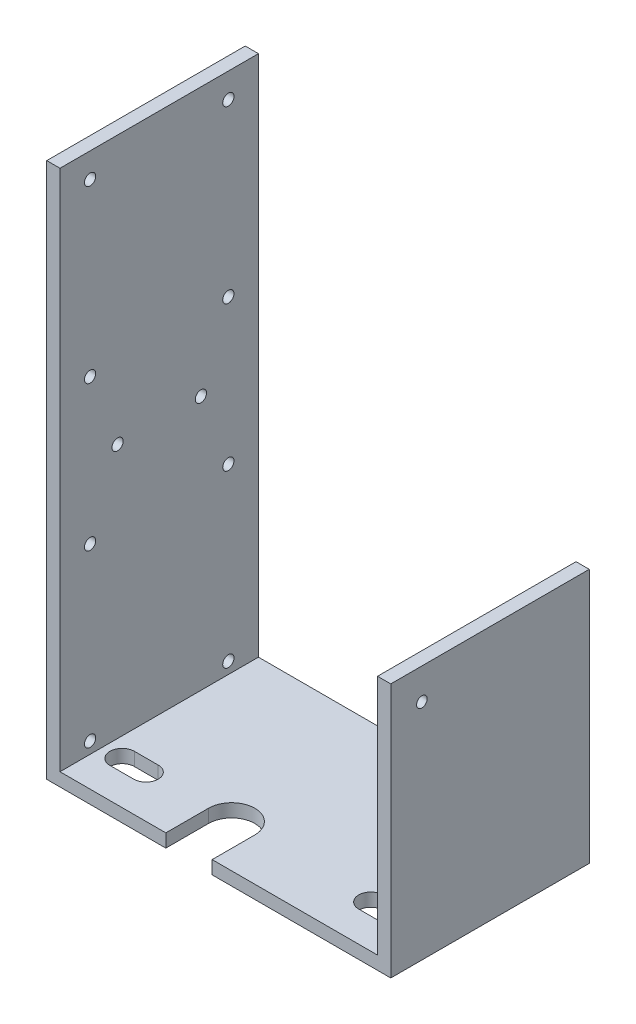
SolidWorks part; units mm, degrees
ref_plane "Alzado" through (0, 0, 0) normal (0, 0, 1) x (1, 0, 0)
ref_plane "Planta" through (0, 0, 0) normal (0, 1, 0) x (1, 0, 0)
ref_plane "Vista lateral" through (0, 0, 0) normal (1, 0, 0) x (0, 0, -1)
sketch "Croquis1" plane through (0, 0, 0) normal (0, 0, 1) x (1, 0, 0)
  line L0 (0, 0) -> (0, 81)
  line L1 (0, 81) -> (2, 81)
  line L2 (2, 81) -> (2, 2)
  line L3 (2, 2) -> (50, 2)
  line L4 (50, 2) -> (50, 38.5)
  line L5 (50, 38.5) -> (52, 38.5)
  line L6 (52, 38.5) -> (52, 0)
  line L7 (52, 0) -> (0, 0)
  dimension "D1" = 81
  dimension "D2" = 2
  dimension "D3" = 52
  dimension "D4" = 38.5
  dimension "D5" = 2
  dimension "D6" = 2
extrude "Saliente-Extruir1" add sketch "Croquis1" along normal blind 30
sketch "Croquis2" plane through (52, 0, 0) normal (1, 0, 0) x (0, 0, -1)
  line L0 (-30, 38.5) -> (0, 38.5) construction
  line L1 (-26.1, 34.6) -> (-24.5, 34.6) construction
  line L2 (-26.1, 34.6) -> (-26.1, 33) construction
  line L3 (-26.1, 33) -> (-24.5, 33) construction
  line L4 (-24.5, 34.6) -> (-24.5, 33) construction
  line L5 (-30, 0) -> (-30, 38.5) construction
  line L6 (-26.1, 34.6) -> (-24.5, 33) construction
  circle A0 centre (-25.3, 33.8) radius 0.8
  dimension "D1" = 3.9
  dimension "D2" = 3.9
  dimension "D3" = 1.6
extrude "Cortar-Extruir1" cut sketch "Croquis2" against normal up to surface (2 mm away) up to face at (50, 20.25, 15)
sketch "Croquis3" plane through (0, 0, 0) normal (-1, 0, 0) x (0, 0, 1)
  line L0 (30, 81) -> (0, 81) construction
  line L1 (3.7, 78.1) -> (26.3, 78.1) construction
  line L2 (3.7, 78.1) -> (3.7, 50.6) construction
  line L3 (3.7, 50.6) -> (26.3, 50.6) construction
  line L4 (26.3, 78.1) -> (26.3, 50.6) construction
  line L5 (0, 81) -> (0, 0) construction
  line L6 (30, 81) -> (30, 0) construction
  line L7 (0, 40.5) -> (30, 40.5) construction
  circle A0 centre (4.55, 77.25) radius 0.85
  circle A1 centre (25.45, 77.25) radius 0.85
  circle A2 centre (25.45, 51.45) radius 0.85
  circle A3 centre (4.55, 51.45) radius 0.85
  circle A4 centre (25.45, 29.55) radius 0.85
  circle A5 centre (4.55, 29.55) radius 0.85
  circle A6 centre (25.45, 3.75) radius 0.85
  circle A7 centre (4.55, 3.75) radius 0.85
  circle A8 centre (8.7, 40.5) radius 0.85
  circle A9 centre (21.3, 40.5) radius 0.85
  dimension "D5" = 1.7
  dimension "D1" = 2.9
  dimension "D2" = 3.7
  dimension "D3" = 3.7
  dimension "D4" = 27.5
  dimension "D6" = 8.7
  dimension "D7" = 8.7
extrude "Cortar-Extruir2" cut sketch "Croquis3" against normal up to surface (2 mm away) up to face at (2, 41.5, 15)
sketch "Croquis4" plane through (0, 0, 0) normal (0, -1, 0) x (1, 0, 0)
  line L0 (0, 23.55) -> (52, 23.55) construction
  line L1 (0, 30) -> (0, 0) construction
  line L2 (52, 30) -> (52, 0) construction
  line L3 (0, 30) -> (52, 30) construction
  line L4 (4.95, 23.55) -> (8.55, 23.55) construction
  line L5 (4.95, 25.4) -> (8.55, 25.4)
  line L6 (4.95, 21.7) -> (8.55, 21.7)
  line L7 (42.55, 23.55) -> (46.15, 23.55) construction
  line L8 (42.55, 25.4) -> (46.15, 25.4)
  line L9 (42.55, 21.7) -> (46.15, 21.7)
  line L10 (21.5, 23.55) -> (21.5, 30) construction
  line L11 (18, 23.55) -> (18, 30)
  line L12 (25, 23.55) -> (25, 30)
  arc A0 (4.95, 25.4) -> (4.95, 21.7) centre (4.95, 23.55) ccw
  arc A1 (8.55, 21.7) -> (8.55, 25.4) centre (8.55, 23.55) ccw
  arc A2 (42.55, 25.4) -> (42.55, 21.7) centre (42.55, 23.55) ccw
  arc A3 (46.15, 21.7) -> (46.15, 25.4) centre (46.15, 23.55) ccw
  arc A4 (18, 23.55) -> (25, 23.55) centre (21.5, 23.55) ccw
  arc A5 (25, 30) -> (18, 30) centre (21.5, 30) ccw
  point P10 (6.75, 23.55)
  point P17 (44.35, 23.55)
  point P24 (21.5, 26.775)
  dimension "D8" = 3.5
  dimension "D1" = 6.45
  dimension "D2" = 3.7
  dimension "D3" = 3.7
  dimension "D4" = 5.85
  dimension "D5" = 4.95
  dimension "D6" = 3.6
  dimension "D7" = 3.6
  dimension "D9" = 27
extrude "Cortar-Extruir3" cut sketch "Croquis4" against normal up to surface (2 mm away) up to face at (26, 2, 15)
